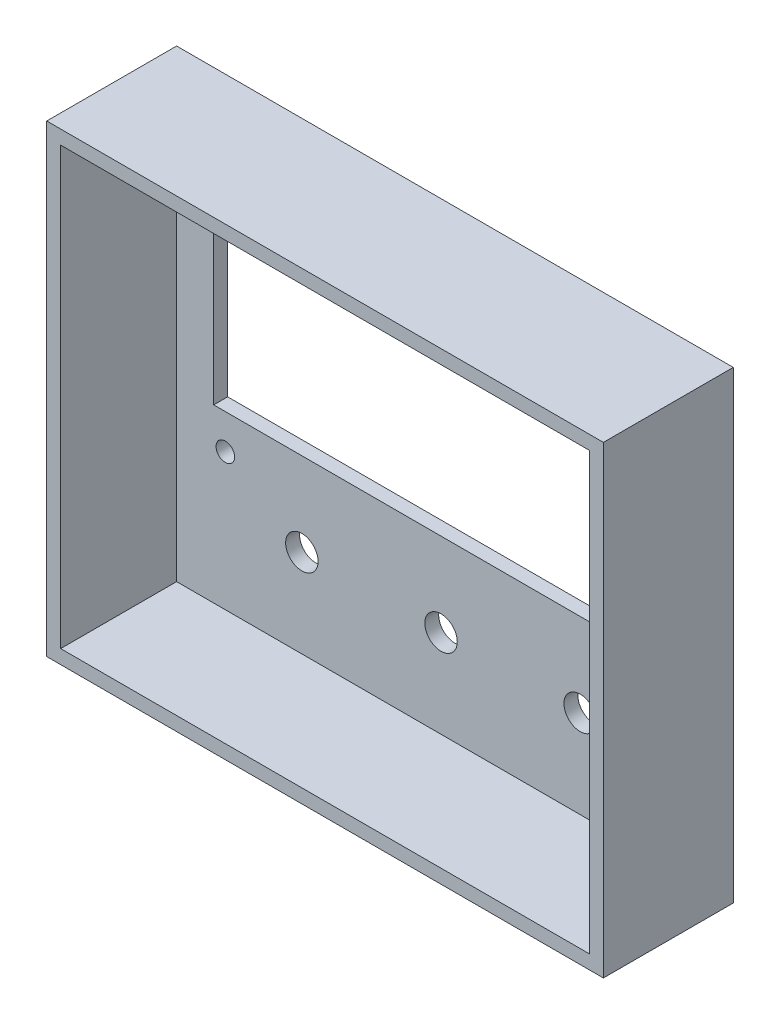
SolidWorks part; units mm, degrees
ref_plane "Alzado" through (0, 0, 0) normal (0, 0, 1) x (1, 0, 0)
ref_plane "Planta" through (0, 0, 0) normal (0, 1, 0) x (1, 0, 0)
ref_plane "Vista lateral" through (0, 0, 0) normal (1, 0, 0) x (0, 0, -1)
sketch "Croquis1" plane through (0, 0, 0) normal (0, 0, 1) x (1, 0, 0)
  line L0 (0, 0) -> (0, 100)
  line L1 (0, 100) -> (120, 100)
  line L2 (120, 100) -> (120, 0)
  line L3 (120, 0) -> (0, 0)
extrude "Saliente-Extruir1" add sketch "Croquis1" along normal blind 3
sketch "Croquis2" plane through (0, 0, 3) normal (0, 0, 1) x (1, 0, 0)
  line L0 (11, 60) -> (11, 80)
  line L7 (11, 80) -> (109, 80)
  line L8 (109, 80) -> (109, 40)
  line L9 (109, 40) -> (11, 40)
  line L10 (11, 40) -> (11, 80)
  circle A0 centre (13.5, 87.5) radius 2
  circle A1 centre (106.5, 87.5) radius 2
  circle A2 centre (106.5, 32.5) radius 2
  circle A3 centre (13.5, 32.5) radius 2
  circle A4 centre (30, 22) radius 3.5
  circle A5 centre (60, 22) radius 3.5
  circle A6 centre (90, 22) radius 3.5
extrude "Cortar-Extruir1" cut sketch "Croquis2" against normal blind 3 contours L10 L9 L8 L7 L0 | A0 | A1 | A2 | A3 | A4 | A5 | A6
sketch "Croquis3" plane through (0, 0, 3) normal (0, 0, 1) x (1, 0, 0)
  line L1 (0, 100) -> (120, 100)
  line L2 (0, 100) -> (0, 0)
  line L3 (0, 0) -> (120, 0)
  line L4 (120, 100) -> (120, 0)
  line L6 (3, 97) -> (117, 97)
  line L7 (117, 97) -> (117, 3)
  line L8 (117, 3) -> (3, 3)
  line L9 (3, 3) -> (3, 97)
extrude "Saliente-Extruir2" add sketch "Croquis3" along normal blind 25
